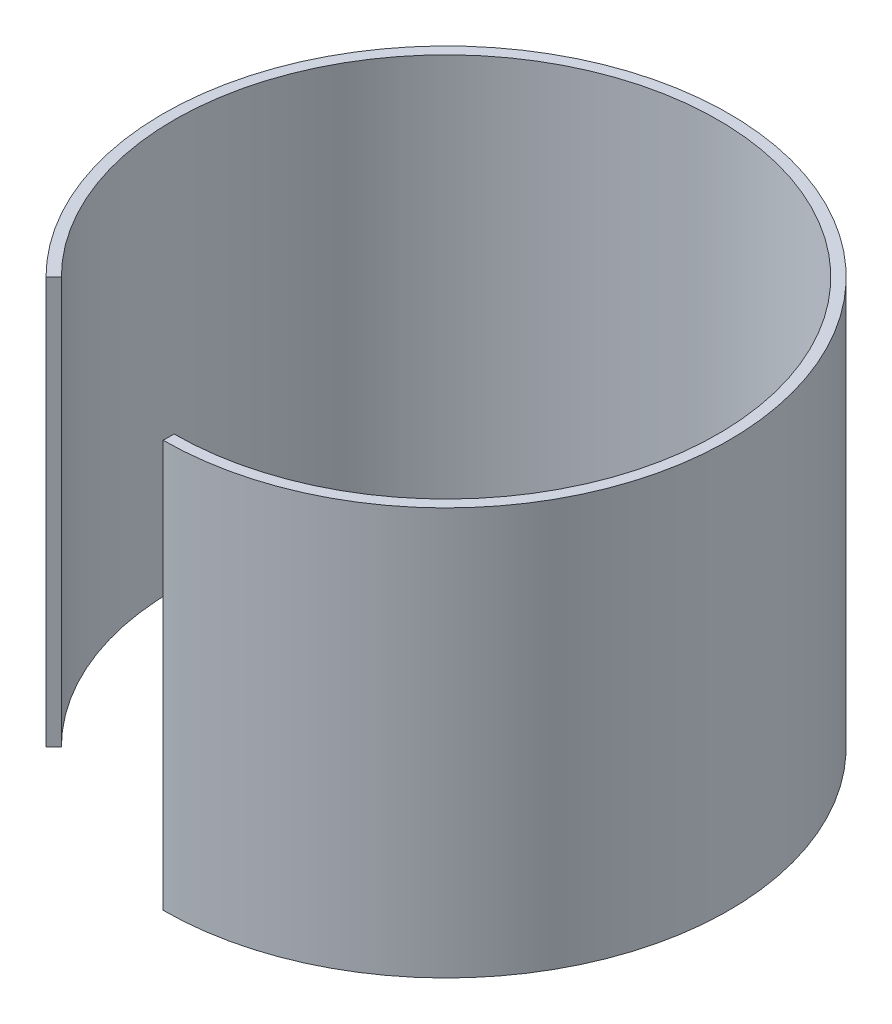
SolidWorks part; units mm, degrees
ref_plane "Plan de face " through (0, 0, 0) normal (0, 0, 1) x (1, 0, 0)
ref_plane "Plan de dessous " through (0, 0, 0) normal (0, 1, 0) x (1, 0, 0)
ref_plane "Plan de droite " through (0, 0, 0) normal (1, 0, 0) x (0, 0, -1)
sketch "Sketch3" plane through (0, 0, 0) normal (0, 1, 0) x (1, 0, 0)
  line L0 (0, -50.12) -> (0, -52.12)
  line L1 (-35.4402, -35.4402) -> (-36.8544, -36.8544)
  arc A0 (0, -50.12) -> (-35.4402, -35.4402) centre (0, 0) ccw
  arc A1 (0, -52.12) -> (-36.8544, -36.8544) centre (0, 0) ccw
  circle A3 centre (0, 0) radius 52.12 construction
  circle A4 centre (0, 0) radius 50.12 construction
  point P4 (47.93, 14.6537)
  point P7 (52.12, 0)
  dimension "D1" = 100.24
  dimension "D3" = 45
  dimension "D2" = 2
extrude "Boss-Extrude1" add sketch "Sketch3" along normal blind 75
